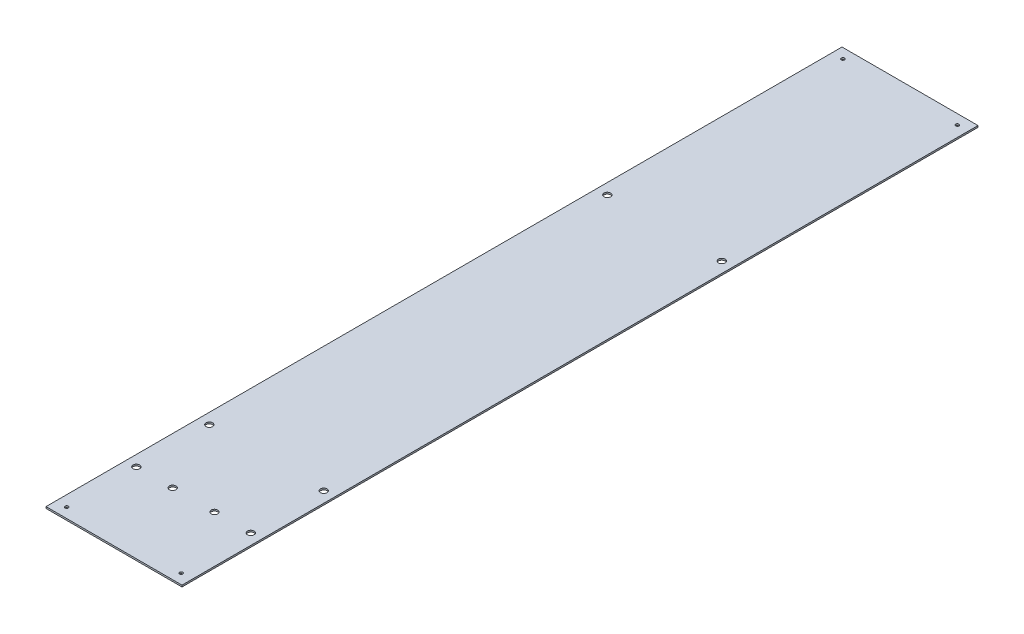
SolidWorks part; units mm, degrees
material "Balsa"
ref_plane "Front Plane" through (0, 0, 0) normal (0, 0, 1) x (1, 0, 0)
ref_plane "Top Plane" through (0, 0, 0) normal (0, 1, 0) x (1, 0, 0)
ref_plane "Right Plane" through (0, 0, 0) normal (1, 0, 0) x (0, 0, -1)
sketch "Sketch1" plane through (0, 0, 0) normal (0, 1, 0) x (1, 0, 0)
  line L1 (-65.0875, -381) -> (65.0875, -381)
  line L2 (-65.0875, -381) -> (-65.0875, 381)
  line L3 (-65.0875, 381) -> (65.0875, 381)
  line L4 (65.0875, -381) -> (65.0875, 381)
  line L5 (-65.0875, -381) -> (65.0875, 381) construction
  line L6 (-65.0875, 381) -> (65.0875, -381) construction
  point P0 (0, 0)
  dimension "D1" = 762
  dimension "D2" = 130.175
extrude "Boss-Extrude1" add sketch "Sketch1" against normal blind 1.5875
sketch "Sketch2" plane through (0, 0, 0) normal (0, 1, 0) x (1, 0, 0)
  line L0 (54.7688, -381) -> (54.7688, 381) construction
  line L1 (-65.0875, -381) -> (65.0875, -381) construction
  line L2 (65.0875, 381) -> (-65.0875, 381) construction
  line L3 (65.0875, -381) -> (65.0875, 381) construction
  circle A0 centre (54.7688, -371.475) radius 1.5875
  circle A1 centre (54.7688, -234.95) radius 3.175
  circle A2 centre (54.7688, 371.475) radius 1.5875
  circle A3 centre (54.7687, 146.05) radius 3.175
  circle A4 centre (54.7688, -304.8) radius 3.175
  circle A5 centre (20, -304.8) radius 3.175
  dimension "D4" = 3.175
  dimension "D5" = 6.35
  dimension "D8" = 3.175
  dimension "D9" = 6.35
  dimension "D10" = 6.35
  dimension "D12" = 6.35
  dimension "D1" = 10.3187
  dimension "D2" = 9.525
  dimension "D3" = 136.525
  dimension "D6" = 9.525
  dimension "D7" = 381
  dimension "D11" = 69.85
  dimension "D13" = 34.7687
extrude "Cut-Extrude2" cut sketch "Sketch2" against normal through all
ref_plane "Plane1" through (0, 0, 0) normal (1, 0, 0) x (0, 0, -1)
mirror "Mirror2" about plane through (0, 0, 0) normal (1, 0, 0) of "Cut-Extrude2"
